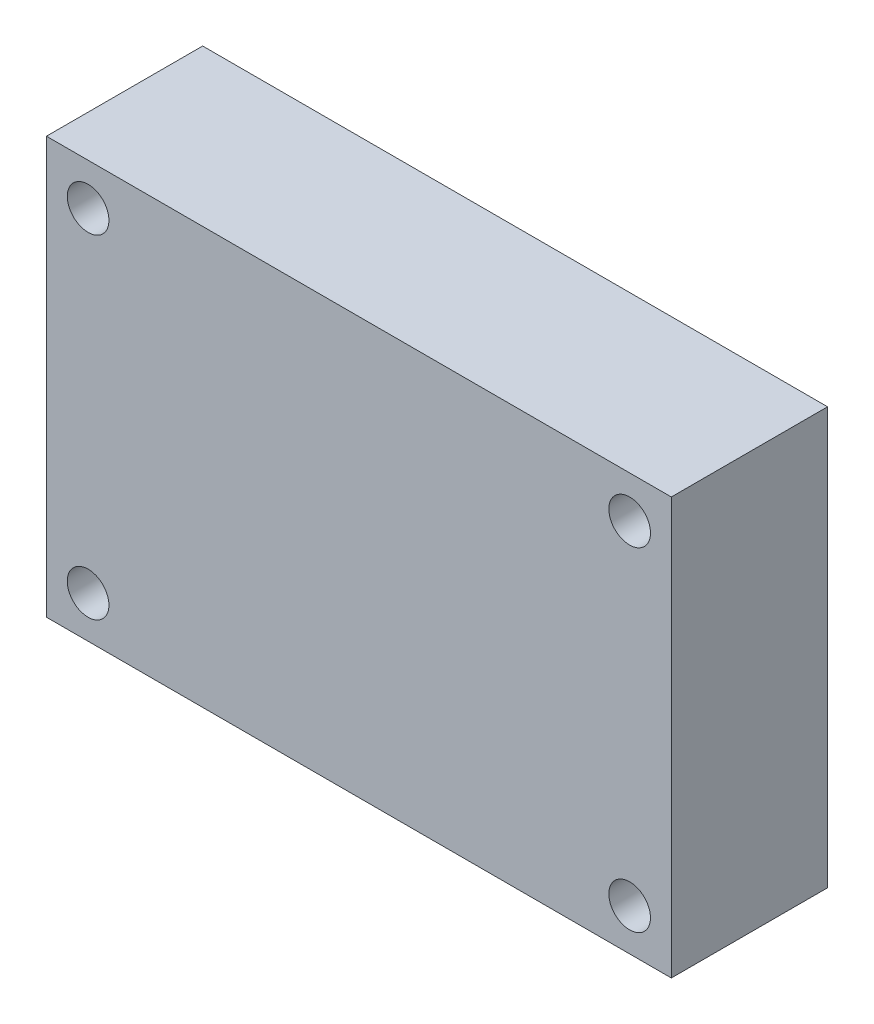
SolidWorks part; units mm, degrees
ref_plane "Plan de face" through (0, 0, 0) normal (0, 0, 1) x (1, 0, 0)
ref_plane "Plan de dessus" through (0, 0, 0) normal (0, 1, 0) x (1, 0, 0)
ref_plane "Plan de droite" through (0, 0, 0) normal (1, 0, 0) x (0, 0, -1)
sketch "Esquisse1" plane through (0, 0, 0) normal (0, 0, 1) x (1, 0, 0)
  line L1 (-30, -20) -> (30, -20)
  line L2 (-30, -20) -> (-30, 20)
  line L3 (-30, 20) -> (30, 20)
  line L4 (30, -20) -> (30, 20)
  line L5 (-30, -20) -> (30, 20) construction
  line L6 (-30, 20) -> (30, -20) construction
  point P0 (0, 0)
  dimension "D1" = 60
  dimension "D2" = 40
extrude "Boss.-Extru.1" add sketch "Esquisse1" along normal blind 15
sketch "Esquisse3" plane through (0, 0, 0) normal (0, 0, -1) x (-1, 0, 0)
  line L0 (-36.7899, 16) -> (35.6636, 16) construction
  line L1 (-30, 20) -> (30, 20) construction
  line L2 (-45.1427, -16) -> (33.3173, -16) construction
  line L3 (30, -20) -> (-30, -20) construction
  line L4 (-26, 22.2898) -> (-26, -22.2898) construction
  line L5 (-30, -20) -> (-30, 20) construction
  line L6 (26, 21.7267) -> (26, -24.2607) construction
  line L7 (30, 20) -> (30, -20) construction
  circle A0 centre (-26, 16) radius 2
  circle A1 centre (26, 16) radius 2
  circle A2 centre (-26, -16) radius 2
  circle A3 centre (26, -16) radius 2
  dimension "D5" = 4
  dimension "D1" = 4
  dimension "D2" = 4
  dimension "D3" = 4
  dimension "D4" = 4
extrude "Enlèv. mat.-Extru.1" cut sketch "Esquisse3" against normal blind 25 contours A0 | A2 | A3 | A1
sketch "Esquisse4" plane through (0, 0, 0) normal (0, 0, -1) x (-1, 0, 0)
  arc A0 (-15.2961, -5.3043) -> (13.5649, 2.161) centre (2.1475, -13.2202) cw construction
  arc A1 (18.3332, 8.5847) -> (-22.581, -1.9983) centre (2.1475, -13.2202) ccw
  arc A2 (8.7967, -4.2627) -> (-8.0111, -8.6102) centre (2.1475, -13.2202) ccw
  arc A3 (8.7967, -4.2627) -> (18.3332, 8.5847) centre (13.5649, 2.161) ccw
  arc A4 (-22.581, -1.9983) -> (-8.0111, -8.6102) centre (-15.2961, -5.3043) ccw
  point P3 (-2.6495, 5.3251)
  dimension "D1" = 8
extrude "Enlèv. mat.-Extru.2" cut sketch "Esquisse4" against normal blind 10
fillet "Congé1" radius 1 4 edges at (-19.9886, -2.6073, 10) (0.6461, -2.42, 10) (18.602, -12.5893, 10) (4.6529, 13.0702, 10)
